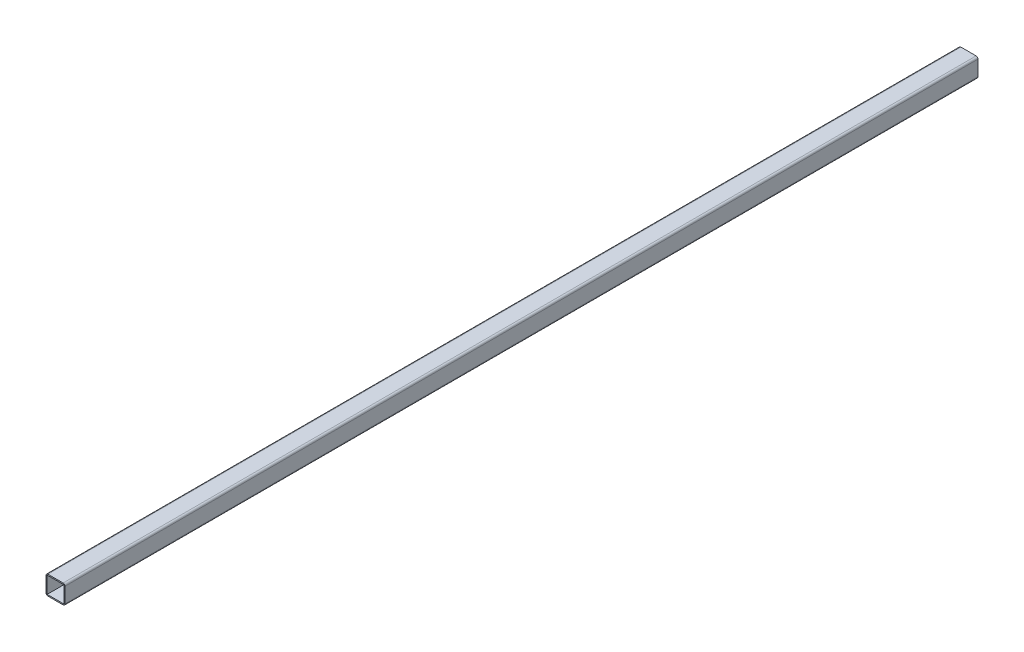
SolidWorks part; units mm, degrees
ref_plane "Front Plane" through (0, 0, 0) normal (0, 0, 1) x (1, 0, 0)
ref_plane "Top Plane" through (0, 0, 0) normal (0, 1, 0) x (1, 0, 0)
ref_plane "Right Plane" through (0, 0, 0) normal (1, 0, 0) x (0, 0, -1)
sketch "Sketch1" plane through (0, 0, 0) normal (0, 0, 1) x (1, 0, 0)
  line L1 (-25.4, 25.4) -> (25.4, 25.4)
  line L2 (-25.4, 25.4) -> (-25.4, -25.4)
  line L3 (-25.4, -25.4) -> (25.4, -25.4)
  line L4 (25.4, 25.4) -> (25.4, -25.4)
  line L5 (-25.4, 25.4) -> (25.4, -25.4) construction
  line L6 (-25.4, -25.4) -> (25.4, 25.4) construction
  line L7 (-22.225, 22.225) -> (22.225, 22.225)
  line L8 (-22.225, 22.225) -> (-22.225, -22.225)
  line L9 (-22.225, -22.225) -> (22.225, -22.225)
  line L10 (22.225, 22.225) -> (22.225, -22.225)
  line L11 (-22.225, 22.225) -> (22.225, -22.225) construction
  line L12 (-22.225, -22.225) -> (22.225, 22.225) construction
  point P0 (0, 0)
  point P5 (0, 0)
  dimension "D1" = 50.8
  dimension "D2" = 50.8
  dimension "D3" = 3.175
extrude "Boss-Extrude1" add sketch "Sketch1" along normal blind 2438.4
fillet "Fillet1" radius 5 4 edges at (25.4, -25.4, 1219.2) (-25.4, -25.4, 1219.2) (-25.4, 25.4, 1219.2) (25.4, 25.4, 1219.2)
